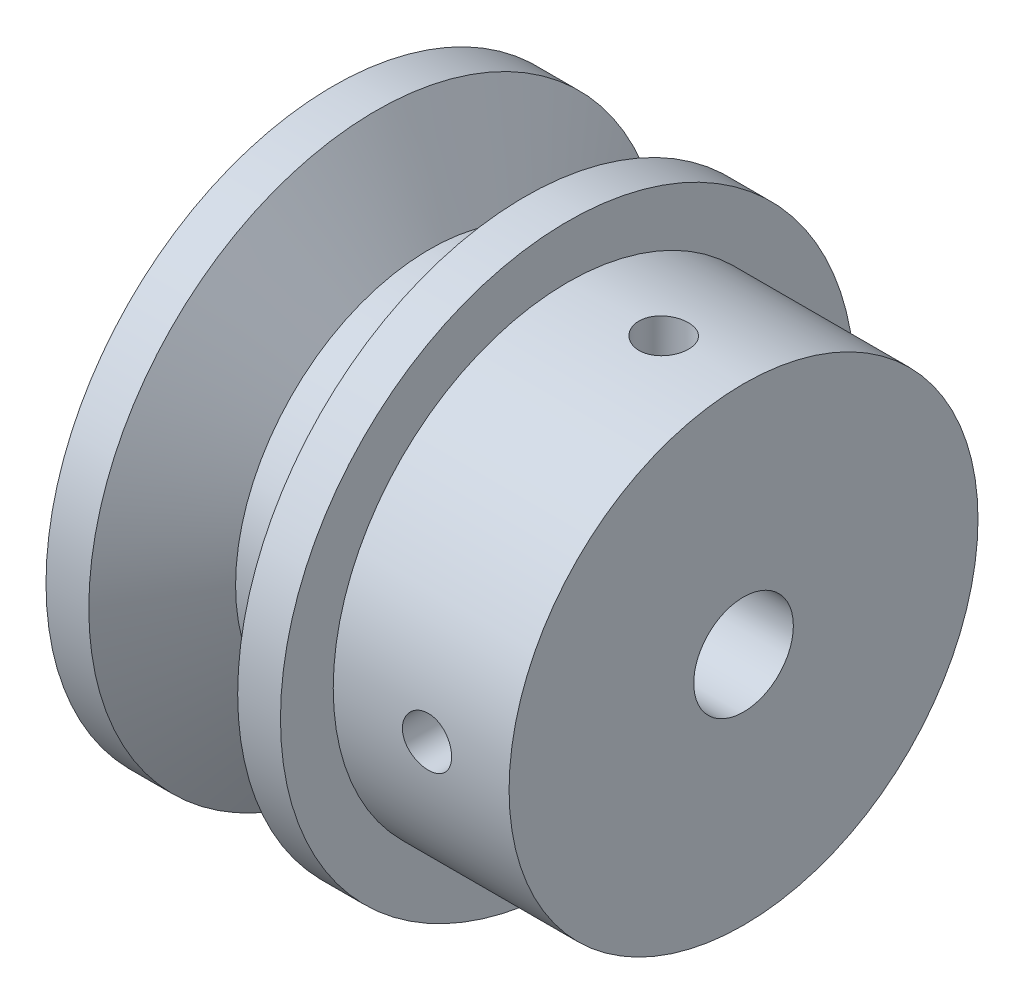
SolidWorks part; units mm, degrees
material "Aleación 1060"
ref_plane "Front" through (0, 0, 0) normal (0, 0, 1) x (1, 0, 0)
ref_plane "Top" through (0, 0, 0) normal (0, 1, 0) x (1, 0, 0)
ref_plane "Right" through (0, 0, 0) normal (1, 0, 0) x (0, 0, -1)
sketch "Croquis1" plane through (0, 0, 0) normal (0, 0, 1) x (1, 0, 0)
  line L0 (0, 0) -> (35, 0)
  line L1 (35, 0) -> (35, 20)
  line L2 (35, 20) -> (20, 20)
  line L3 (20, 20) -> (20, 24.5)
  line L5 (0, 24.5) -> (0, 0)
  line L6 (0, 24.5) -> (3.65, 24.5)
  line L9 (8.2327, 16.5625) -> (11.7673, 16.5625)
  line L11 (3.65, 24.5) -> (12.9824, 18.6672) construction
  line L12 (7.0176, 18.6672) -> (16.35, 24.5) construction
  line L13 (16.35, 24.5) -> (20, 24.5)
  line L14 (3.65, 24.5) -> (8.2327, 16.5625)
  line L15 (8.2327, 16.5625) -> (10, 16.5625)
  line L16 (10, 16.5625) -> (10, 20.5312) construction
  line L17 (16.35, 24.5) -> (11.7673, 16.5625)
  point P11 (10, 20.5312)
  dimension "D1" = 24.5
  dimension "D2" = 20
  dimension "D3" = 15
  dimension "D4" = 20
  dimension "D5" = 12.7
  dimension "D6" = 60
revolve "Revolución1" add sketch "Croquis1" angle 360 about L0
sketch "Croquis2" plane through (35, 0, 0) normal (1, 0, 0) x (0, 0, -1)
  circle A0 centre (0, 0) radius 5
  dimension "D1" = 10
extrude "Cortar-Extruir1" [suppressed] cut sketch "Croquis2" against normal up to surface (35 mm away)
hole_wizard "Perforador para roscar para macho de roscar para M51" positions "Croquis3D1" profile "Croquis3" hole size "M5" standard "ISO"
sketch3d "Croquis3D1"
  line L1 (28, 19.9991, -0.1929) -> (0, 0, 0) construction
  line L4 (0, 0, 0) -> (0, 0, 20) construction
  point P4 (28, 0, 20)
  point P6 (28, 19.9991, -0.1929)
  dimension "D1" = 7
  dimension "D2" = 7
cosmetic thread "Rosca cosmética1" parameters "D2"=5
cosmetic thread "Rosca cosmética2" parameters "D2"=5
sketch "Croquis3" plane through (28, 0, 20) normal (1, 0, 0) x (0, -1, 0)
  line L0 (0, 0) -> (0, 21.2618)
  line L1 (0, 21.2618) -> (2.1, 20)
  line L2 (2.1, 20) -> (2.1, 0)
  line L5 (2.1, 0) -> (0, 0)
  line L10 (0, 21.2618) -> (-2.1, 20) construction
  line L11 (0, -6.35) -> (0, 107.95) construction
  dimension "Diámetro de taladro" = 4.2
  dimension "Profundidad de taladro" = 20
  dimension "Ángulo de perforador" = 118
hole_wizard "Perforador para roscar para macho de roscar para M101" positions "Croquis4" profile "Croquis5" hole size "M10" standard "ISO"
sketch "Croquis4" plane through (35, 0, 0) normal (1, 0, 0) x (0, 0, -1)
  point P0 (0, 0)
sketch "Croquis5" plane through (35, 0, 0) normal (0, 1, 0) x (0, 0, -1)
  line L0 (0, 0) -> (0, 42.5537)
  line L1 (0, 42.5537) -> (4.25, 40)
  line L2 (4.25, 40) -> (4.25, 0)
  line L5 (4.25, 0) -> (0, 0)
  line L10 (0, 42.5537) -> (-4.25, 40) construction
  line L11 (0, -6.35) -> (0, 107.95) construction
  dimension "Diámetro de taladro" = 8.5
  dimension "Profundidad de taladro" = 40
  dimension "Ángulo de perforador" = 118
cosmetic thread "Rosca cosmética3" parameters "D2"=10
